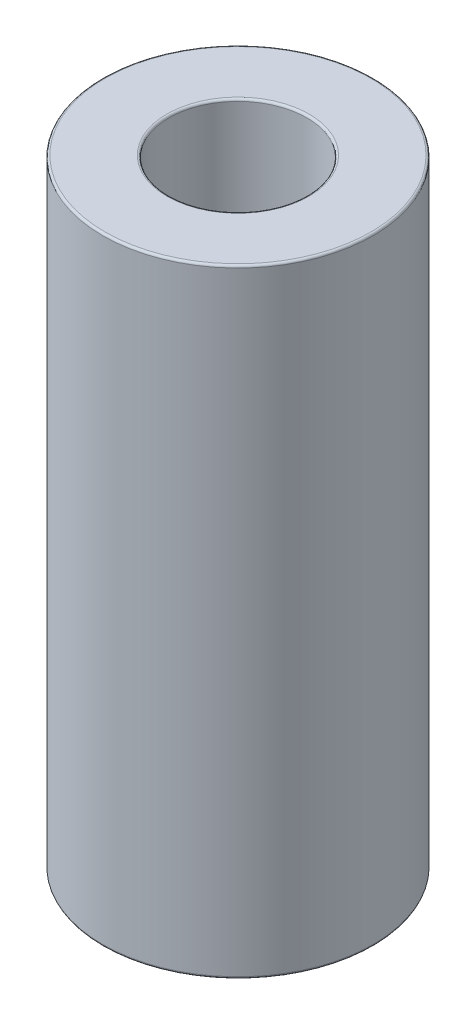
SolidWorks part; units mm, degrees
ref_plane "Front Plane" through (0, 0, 0) normal (0, 0, 1) x (1, 0, 0)
ref_plane "Top Plane" through (0, 0, 0) normal (0, 1, 0) x (1, 0, 0)
ref_plane "Right Plane" through (0, 0, 0) normal (1, 0, 0) x (0, 0, -1)
sketch "Sketch1" plane through (0, 0, 0) normal (0, 1, 0) x (1, 0, 0)
  circle A0 centre (0, 0) radius 6.125
  dimension "D1" = 12.25
extrude "Extrude-Thin1" add sketch "Sketch1" along normal blind 28 thin thin type one direction reverse wall 3
fillet "Fillet1" radius 0.1 4 edges at (3.125, 28, 0) (0, 28, 6.125) (3.125, 0, 0) (0, 0, 6.125)
